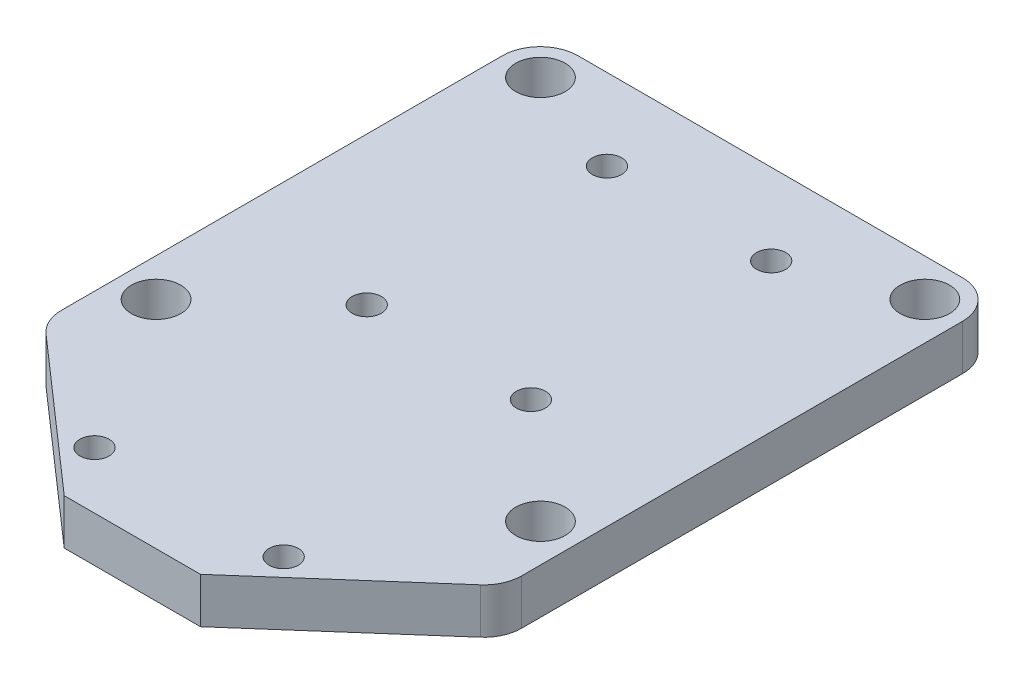
SolidWorks part; units mm, degrees
ref_plane "Front Plane" through (0, 0, 0) normal (0, 0, 1) x (1, 0, 0)
ref_plane "Top Plane" through (0, 0, 0) normal (0, 1, 0) x (1, 0, 0)
ref_plane "Right Plane" through (0, 0, 0) normal (1, 0, 0) x (0, 0, -1)
sketch "Sketch1" plane through (0, 0, 0) normal (0, 1, 0) x (1, 0, 0)
  line L0 (-9, -42.15) -> (-30.4, -23.3644)
  line L1 (30.4, -42.15) -> (9, -42.15) construction
  line L2 (30.4, -42.15) -> (30.4, -23.3644) construction
  line L3 (30.4, 42.15) -> (-30.4, 42.15)
  line L4 (-30.4, -42.15) -> (-30.4, -23.3644) construction
  line L5 (30.4, -42.15) -> (-30.4, 42.15) construction
  line L6 (30.4, 42.15) -> (-30.4, -42.15) construction
  line L7 (9, -42.15) -> (30.4, -23.3644)
  line L8 (-30.4, -23.3644) -> (-30.4, 42.15)
  line L9 (30.4, -23.3644) -> (30.4, 42.15)
  line L10 (9, -42.15) -> (-9, -42.15)
  line L11 (-9, -42.15) -> (-30.4, -42.15) construction
  point P0 (0, 0)
  point P11 (0, -42.15)
  dimension "D1" = 84.3
  dimension "D2" = 60.8
  dimension "D3" = 18.7856
  dimension "D4" = 18
extrude "Boss-Extrude1" add sketch "Sketch1" along normal blind 6
fillet "Fillet1" radius 5 4 edges at (-30.4, 3, -42.15) (30.4, 3, -42.15) (-30.4, 3, 23.3644) (30.4, 3, 23.3644)
hole_wizard "#24 (0.152) Diameter Hole1" positions "Sketch2" profile "Sketch3" hole size "#24" standard "ANSI Inch" end condition through all
sketch "Sketch2" plane through (0, 6, 0) normal (0, 1, 0) x (1, 0, 0)
  point P0 (10.85, -0.325)
  point P3 (-10.85, -0.325)
  point P6 (-10.85, 31.425)
  point P9 (10.85, 31.425)
  point P12 (12.5, -34.65)
  point P15 (-12.5, -34.65)
  dimension "D1" = 21.7
  dimension "D2" = 10.85
  dimension "D3" = 31.75
  dimension "D4" = 0.325
  dimension "D5" = 34.65
  dimension "D6" = 25
  dimension "D7" = 12.5
sketch "Sketch3" plane through (10.85, 6, 0.325) normal (1, 0, 0) x (0, 0, 1)
  line L0 (0, 0) -> (0, 6)
  line L1 (0, 6) -> (1.9304, 6)
  line L2 (1.9304, 6) -> (1.9304, 0)
  line L5 (1.9304, 0) -> (0, 0)
  line L11 (0, -6.35) -> (0, 107.95) construction
  dimension "Thru Hole Dia." = 3.8608
  dimension "Thru Hole Depth" = 6
hole_wizard "F (0.257) Diameter Hole1" positions "Sketch4" profile "Sketch5" hole size "F" standard "ANSI Inch" end condition through all
sketch "Sketch4" plane through (0, 6, 0) normal (0, 1, 0) x (1, 0, 0)
  line L0 (-25.4, 37.185) -> (-25.4, 42.15)
  line L1 (25.4, 42.15) -> (-25.4, 42.15) construction
  point P0 (25.4, 37.185)
  point P2 (-25.4, 37.185)
  point P4 (-25.4, -13.615)
  point P6 (25.4, -13.615)
  point P34 (0, 0)
  point P35 (0, 0)
  point P36 (0, 0)
  point P37 (0, 0)
  dimension "D1" = 50.8
  dimension "D2" = 50.8
  dimension "D3" = 25.4
  dimension "D4" = 37.185
sketch "Sketch5" plane through (25.4, 6, -37.185) normal (1, 0, 0) x (0, 0, 1)
  line L0 (0, 0) -> (0, 6)
  line L1 (0, 6) -> (3.2639, 6)
  line L2 (3.2639, 6) -> (3.2639, 0)
  line L5 (3.2639, 0) -> (0, 0)
  line L11 (0, -6.35) -> (0, 107.95) construction
  dimension "Thru Hole Dia." = 6.5278
  dimension "Thru Hole Depth" = 6
equation "\"D2@Sketch2\"=\"D1@Sketch2\"/2"
equation "\"D3@Sketch4\"=\"D2@Sketch4\"/2"
equation "\"D7@Sketch2\"=\"D6@Sketch2\"/2"
